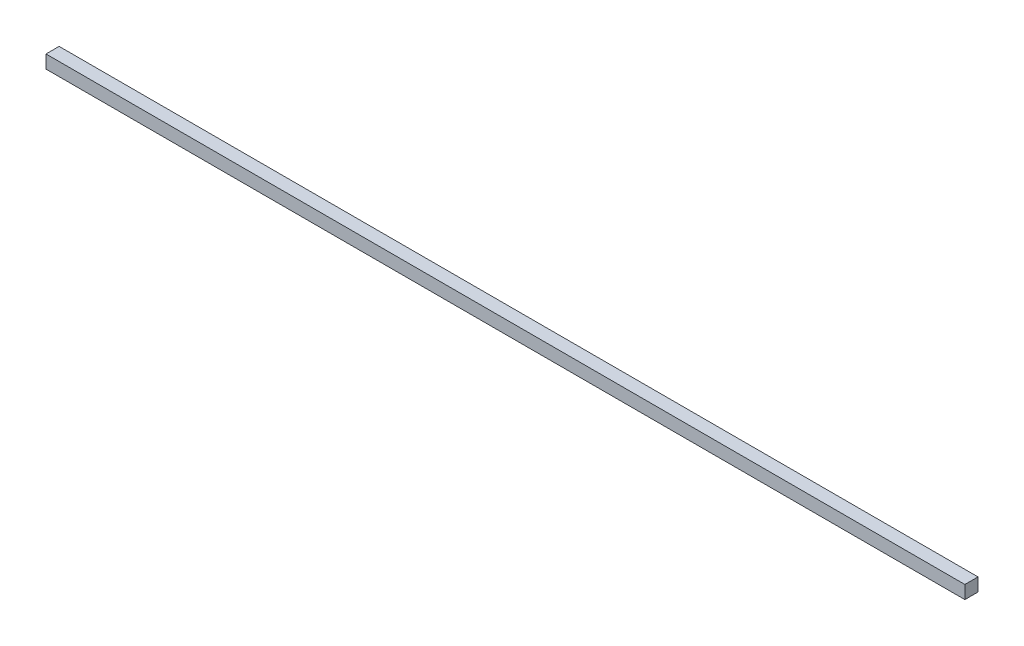
SolidWorks part; units mm, degrees
ref_plane "Front Plane" through (0, 0, 0) normal (0, 0, 1) x (1, 0, 0)
ref_plane "Top Plane" through (0, 0, 0) normal (0, 1, 0) x (1, 0, 0)
ref_plane "Right Plane" through (0, 0, 0) normal (1, 0, 0) x (0, 0, -1)
sketch "Sketch1" plane through (0, 0, 0) normal (0, 1, 0) x (1, 0, 0)
  line L1 (70, -1) -> (-70, -1)
  line L2 (70, -1) -> (70, 1)
  line L3 (70, 1) -> (-70, 1)
  line L4 (-70, -1) -> (-70, 1)
  line L5 (70, -1) -> (-70, 1) construction
  line L6 (70, 1) -> (-70, -1) construction
  point P0 (0, 0)
  dimension "D1" = 2
  dimension "D2" = 140
extrude "Boss-Extrude1" add sketch "Sketch1" along normal blind 2
